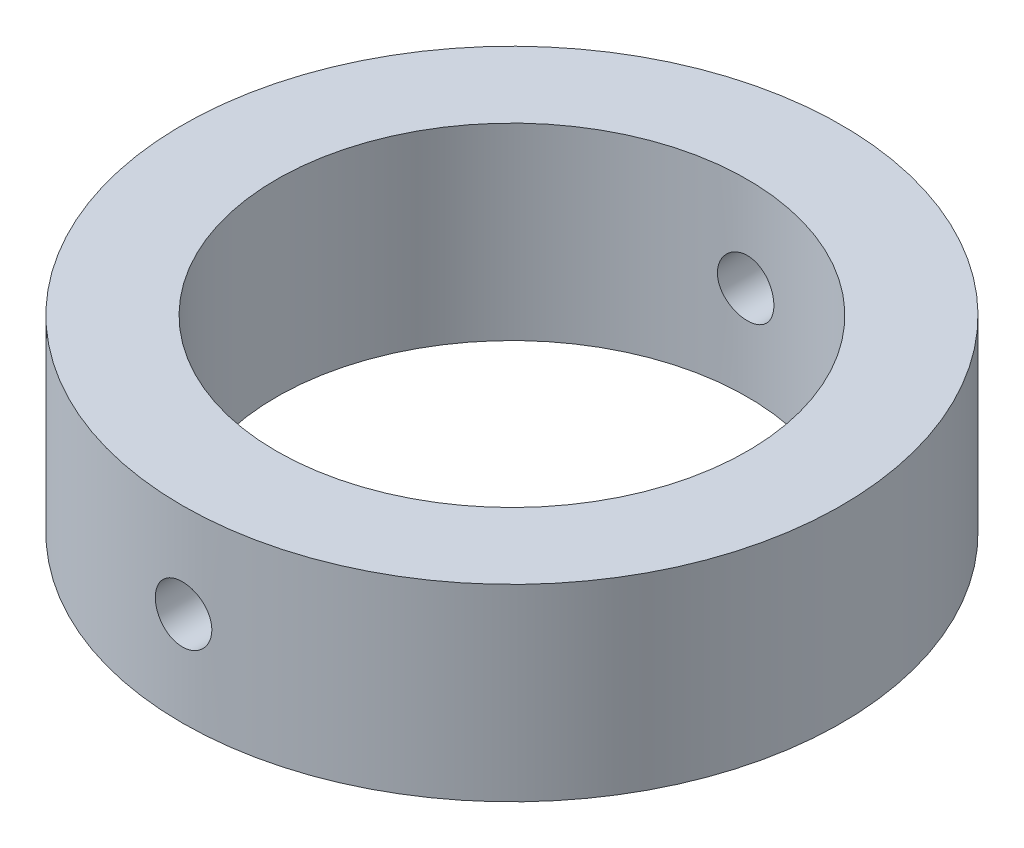
SolidWorks part; units mm, degrees
ref_plane "Front Plane" through (0, 0, 0) normal (0, 0, 1) x (1, 0, 0)
ref_plane "Top Plane" through (0, 0, 0) normal (0, 1, 0) x (1, 0, 0)
ref_plane "Right Plane" through (0, 0, 0) normal (1, 0, 0) x (0, 0, -1)
sketch "Sketch1" plane through (0, 0, 0) normal (0, 1, 0) x (1, 0, 0)
  circle A0 centre (0, 0) radius 250
  circle A1 centre (0, 0) radius 350
  dimension "D1" = 700
  dimension "D2" = 500
extrude "Boss-Extrude1" add sketch "Sketch1" along normal blind 200
sketch "Sketch2" plane through (0, 0, 0) normal (0, 0, 1) x (1, 0, 0)
  line L0 (250, 200) -> (-250, 200) construction
  circle A0 centre (0, 100) radius 30
  dimension "D1" = 60
  dimension "D2" = 100
extrude "Cut-Extrude1" cut sketch "Sketch2" against normal mid plane 907
